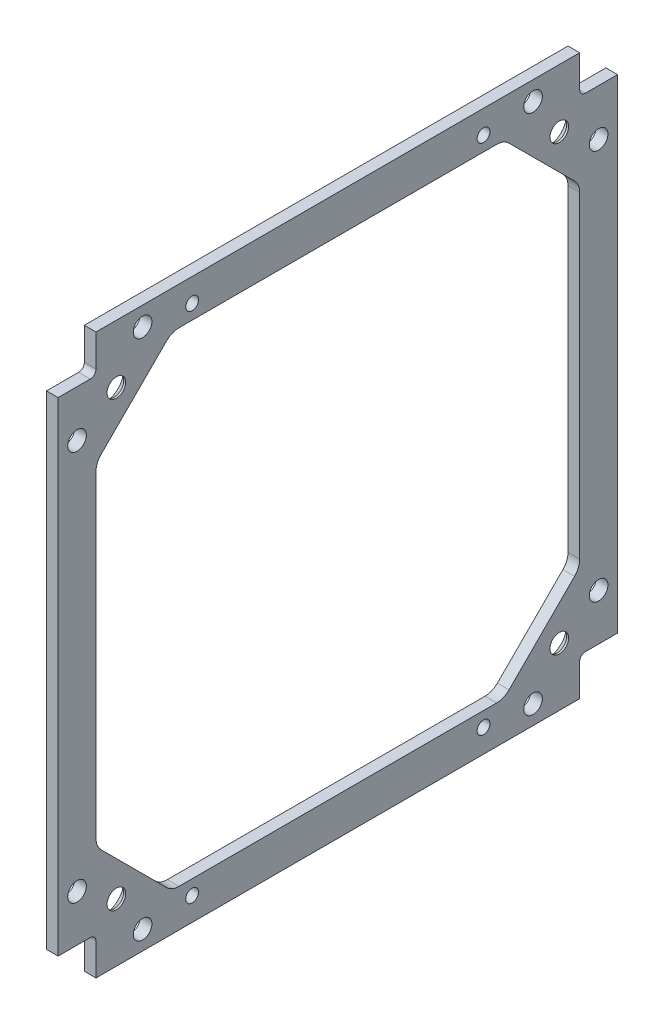
SolidWorks part; units mm, degrees
ref_plane "Front Plane" through (0, 0, 0) normal (0, 0, 1) x (1, 0, 0)
ref_plane "Top Plane" through (0, 0, 0) normal (0, 1, 0) x (1, 0, 0)
ref_plane "Right Plane" through (0, 0, 0) normal (1, 0, 0) x (0, 0, -1)
sketch "Sketch2" plane through (-51.4936, 0, 0) normal (-1, 0, 0) x (0, 0, 1)
  line L0 (0.9347, 3.4519) -> (7.4347, 3.4519)
  line L1 (7.4347, 3.4519) -> (7.4347, 86.4519)
  line L2 (0.9347, 92.9519) -> (-82.0653, 92.9519)
  line L3 (-88.5653, 86.4519) -> (-88.5653, 3.4519)
  line L4 (-82.0653, -3.0481) -> (0.9347, -3.0481)
  line L5 (0.9347, -3.0481) -> (0.9347, 3.4519)
  line L6 (-82.0653, -3.0481) -> (-82.0653, 3.4519)
  line L7 (-82.0653, 3.4519) -> (-88.5653, 3.4519)
  line L9 (-82.0653, 73.4519) -> (-82.0653, 16.4519)
  line L11 (-88.5653, 86.4519) -> (-82.0653, 86.4519)
  line L12 (-82.0653, 92.9519) -> (-82.0653, 86.4519)
  line L13 (-69.0653, 3.4519) -> (-12.0653, 3.4519)
  line L14 (-82.0653, 73.4519) -> (-69.0653, 86.4519)
  line L15 (7.4347, 86.4519) -> (0.9347, 86.4519)
  line L16 (0.9347, 92.9519) -> (0.9347, 86.4519)
  line L17 (0.9347, 16.4519) -> (0.9347, 73.4519)
  line L18 (-12.0653, 86.4519) -> (0.9347, 73.4519)
  line L19 (-12.0653, 86.4519) -> (-69.0653, 86.4519)
  line L28 (-12.0653, 3.4519) -> (0.9347, 16.4519)
  line L29 (-82.0653, 16.4519) -> (-69.0653, 3.4519)
  dimension "D21" = 13
  dimension "D1" = 6.5
  dimension "D2" = 6.5
  dimension "D3" = 6.5
  dimension "D4" = 6.5
  dimension "D5" = 6.5
  dimension "D6" = 6.5
  dimension "D7" = 13
  dimension "D8" = 6.5
  dimension "D9" = 6.5
  dimension "D10" = 13
  dimension "D11" = 6.5
  dimension "D12" = 6.5
  dimension "D14" = 13
  dimension "D15" = 13
  dimension "D16" = 13
  dimension "D17" = 13
  dimension "D18" = 13
  dimension "D19" = 83
  dimension "D20" = 83
extrude "Boss-Extrude2" add sketch "Sketch2" along normal blind 2
hole_wizard "Ø3.2 (3.2) Diameter Hole3" positions "Sketch19" profile "Sketch18" hole size "Ø3.2" standard "Ansi Metric" end condition up to next
sketch "Sketch19" plane through (-53.4936, 0, 0) normal (-1, 0, 0) x (0, 0, 1)
  line L0 (-82.0653, 3.4519) -> (-82.0653, -3.0481) construction
  line L1 (-82.0653, -3.0481) -> (0.9347, -3.0481) construction
  line L2 (-88.5653, 86.4519) -> (-88.5653, 3.4519) construction
  line L4 (-88.5653, 3.4519) -> (-82.0653, 3.4519) construction
  line L5 (0.9347, -3.0481) -> (0.9347, 3.4519) construction
  line L6 (0.9347, 3.4519) -> (7.4347, 3.4519) construction
  line L7 (7.4347, 3.4519) -> (7.4347, 86.4519) construction
  line L8 (7.4347, 86.4519) -> (0.9347, 86.4519) construction
  line L9 (0.9347, 86.4519) -> (0.9347, 92.9519) construction
  line L10 (0.9347, 92.9519) -> (-82.0653, 92.9519) construction
  line L11 (-82.0653, 92.9519) -> (-82.0653, 86.4519) construction
  line L12 (-82.0653, 86.4519) -> (-88.5653, 86.4519) construction
  point P0 (-74.0653, 0.2019)
  point P6 (-85.3153, 11.4519)
  point P8 (-85.3153, 78.4519)
  point P10 (-74.0653, 89.7019)
  point P12 (-7.0653, 89.7019)
  point P14 (4.1847, 78.4519)
  point P16 (4.1847, 11.4519)
  point P18 (-7.0653, 0.2019)
  point P56 (-82.0653, 89.7019)
  point P59 (-85.3153, 86.4519)
  dimension "D1" = 8
  dimension "D2" = 3.25
  dimension "D3" = 3.25
  dimension "D4" = 8
  dimension "D5" = 8
  dimension "D6" = 8
  dimension "D7" = 3.25
  dimension "D8" = 8
  dimension "D9" = 8
  dimension "D10" = 3.25
  dimension "D11" = 8
  dimension "D12" = 8
sketch "Sketch18" plane through (-53.4936, 0.2019, -74.0653) normal (0, 1, 0) x (0, 0, 1)
  line L0 (0, 0) -> (0, 2)
  line L1 (0, 2) -> (1.6, 2)
  line L2 (1.6, 2) -> (1.6, 0)
  line L5 (1.6, 0) -> (0, 0)
  line L11 (0, -6.35) -> (0, 107.95) construction
  dimension "Thru Hole Dia." = 3.2
  dimension "Thru Hole Depth" = 2
hole_wizard "CSK for M3 Flat Countersunk Head Screw5" positions "3DSketch2" profile "Sketch24" countersink size "M3" standard "JIS" end condition up to next
sketch3d "3DSketch2"
  line L0 (-53.4936, 3.4519, -82.0653) -> (-53.4936, -3.0481, -82.0653) construction
  line L1 (-53.4936, 3.4519, -88.5653) -> (-53.4936, 3.4519, -82.0653) construction
  line L2 (-53.4936, 92.9519, -82.0653) -> (-53.4936, 86.4519, -82.0653) construction
  line L3 (-53.4936, 86.4519, -82.0653) -> (-53.4936, 86.4519, -88.5653) construction
  line L4 (-53.4936, 86.4519, 0.9347) -> (-53.4936, 92.9519, 0.9347) construction
  line L5 (-53.4936, 86.4519, 7.4347) -> (-53.4936, 86.4519, 0.9347) construction
  line L6 (-53.4936, -3.0481, 0.9347) -> (-53.4936, 3.4519, 0.9347) construction
  line L7 (-53.4936, 3.4519, 0.9347) -> (-53.4936, 3.4519, 7.4347) construction
  point P0 (-53.4936, 6.9519, -78.5653)
  point P2 (-53.4936, 82.9519, -78.5653)
  point P4 (-53.4936, 82.9519, -2.5653)
  point P19 (-53.4936, 6.9519, -2.5653)
  dimension "D1" = 3.5
  dimension "D2" = 3.5
  dimension "D3" = 3.5
  dimension "D4" = 3.5
  dimension "D5" = 3.5
  dimension "D6" = 3.5
  dimension "D7" = 3.5
  dimension "D8" = 3.5
sketch "Sketch24" plane through (-53.4936, 6.9519, -78.5653) normal (0, 1, 0) x (0, 0, 1)
  line L0 (0, 0) -> (0, 2)
  line L1 (0, 2) -> (1.6, 2)
  line L2 (1.6, 2) -> (1.6, 1.65)
  line L3 (1.6, 1.65) -> (3.25, 0)
  line L5 (3.25, 0) -> (0, 0)
  line L6 (-1.6, 1.65) -> (-3.25, 0) construction
  line L11 (0, -6.35) -> (0, 107.95) construction
  dimension "Thru Hole Dia." = 3.2
  dimension "Thru Hole Depth" = 2
  dimension "Near C'Sink Dia." = 6.5
  dimension "Near C'Sink Angle" = 90
hole_wizard "Ø2.2 (2.2) Diameter Hole1" positions "3DSketch3" profile "Sketch25" hole size "Ø2.2" standard "Ansi Metric" end condition up to next
sketch3d "3DSketch3"
  line L0 (-53.4936, 92.9519, 0.9347) -> (-53.4936, 92.9519, -82.0653) construction
  line L3 (-53.4936, 3.4519, 7.4347) -> (-53.4936, 86.4519, 7.4347) construction
  line L4 (-53.4936, -3.0481, -82.0653) -> (-53.4936, -3.0481, 0.9347) construction
  line L6 (-53.4936, 86.4519, -88.5653) -> (-53.4936, 3.4519, -88.5653) construction
  point P0 (-53.4936, 88.9519, -65.5653)
  point P2 (-53.4936, 88.9519, -15.5653)
  point P4 (-53.4936, 0.9519, -65.5653)
  point P6 (-53.4936, 0.9519, -15.5653)
  dimension "D1" = 4
  dimension "D2" = 23
  dimension "D3" = 4
  dimension "D4" = 23
  dimension "D5" = 4
  dimension "D6" = 23
  dimension "D7" = 23
  dimension "D8" = 4
sketch "Sketch25" plane through (-53.4936, 88.9519, -65.5653) normal (0, 1, 0) x (0, 0, 1)
  line L0 (0, 0) -> (0, 2)
  line L1 (0, 2) -> (1.1, 2)
  line L2 (1.1, 2) -> (1.1, 0)
  line L5 (1.1, 0) -> (0, 0)
  line L11 (0, -6.35) -> (0, 107.95) construction
  dimension "Thru Hole Dia." = 2.2
  dimension "Thru Hole Depth" = 2
fillet "Fillet1" radius 3 8 edges at (-52.4936, 16.4519, 0.9347) (-52.4936, 3.4519, -12.0653) (-52.4936, 3.4519, -69.0653) (-52.4936, 16.4519, -82.0653) (-52.4936, 73.4519, 0.9347) (-52.4936, 86.4519, -12.0653) (-52.4936, 73.4519, -82.0653) (-52.4936, 86.4519, -69.0653)
fillet "Fillet2" radius 1 4 edges at (-52.4936, 3.4519, 0.9347) (-52.4936, 3.4519, -82.0653) (-52.4936, 86.4519, -82.0653) (-52.4936, 86.4519, 0.9347)
sketch "Sketch26" plane through (-51.4936, 0, 0) normal (1, 0, 0) x (0, 0, -1)
  line L1 (-0.9347, 92.9519) -> (-7.4347, 92.9519)
  line L2 (-0.9347, 92.9519) -> (-0.9347, 86.4519)
  line L3 (-0.9347, 86.4519) -> (-7.4347, 86.4519)
  line L4 (-7.4347, 92.9519) -> (-7.4347, 86.4519)
  line L5 (82.0653, 92.9519) -> (88.5653, 92.9519)
  line L6 (82.0653, 92.9519) -> (82.0653, 86.4519)
  line L7 (82.0653, 86.4519) -> (88.5653, 86.4519)
  line L8 (88.5653, 92.9519) -> (88.5653, 86.4519)
  line L9 (82.0653, -3.0481) -> (88.5653, -3.0481)
  line L10 (82.0653, -3.0481) -> (82.0653, 3.4519)
  line L11 (82.0653, 3.4519) -> (88.5653, 3.4519)
  line L12 (88.5653, -3.0481) -> (88.5653, 3.4519)
  line L13 (-7.4347, 3.4519) -> (-0.9347, 3.4519)
  line L14 (-7.4347, 3.4519) -> (-7.4347, -3.0481)
  line L15 (-7.4347, -3.0481) -> (-0.9347, -3.0481)
  line L16 (-0.9347, 3.4519) -> (-0.9347, -3.0481)
